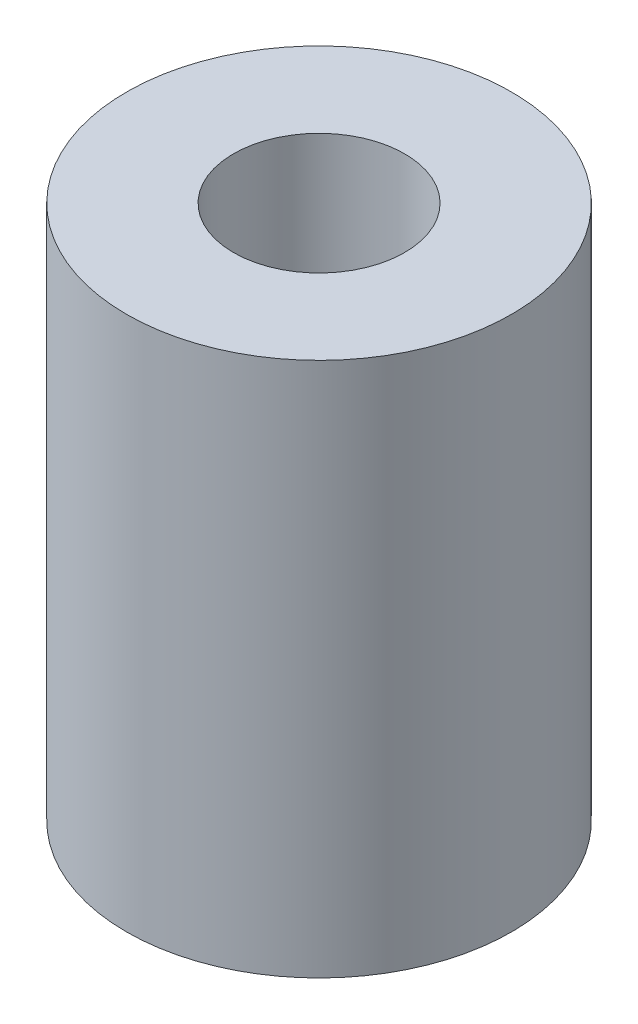
SolidWorks part; units mm, degrees
material "Д16Т ГОСТ 4784-97"
ref_plane "Спереди" through (0, 0, 0) normal (0, 0, 1) x (1, 0, 0)
ref_plane "Сверху" through (0, 0, 0) normal (0, 1, 0) x (1, 0, 0)
ref_plane "Справа" through (0, 0, 0) normal (1, 0, 0) x (0, 0, -1)
sketch "Эскиз1" plane through (0, 0, 0) normal (0, 1, 0) x (1, 0, 0)
  circle A0 centre (0, 0) radius 9
  circle A1 centre (0, 0) radius 2.5
  dimension "D1" = 18
  dimension "D2" = 5
extrude "Бобышка-Вытянуть1" add sketch "Эскиз1" along normal blind 25
sketch "Эскиз2" plane through (0, 25, 0) normal (0, 1, 0) x (1, 0, 0)
  circle A0 centre (0, 0) radius 4
  dimension "D1" = 8
extrude "Вырез-Вытянуть1" cut sketch "Эскиз2" against normal blind 10
sketch "Эскиз3" plane through (0, 0, 0) normal (1, 0, 0) x (0, 0, -1)
  line L0 (0, -5.7993) -> (0, 31.8354) construction
